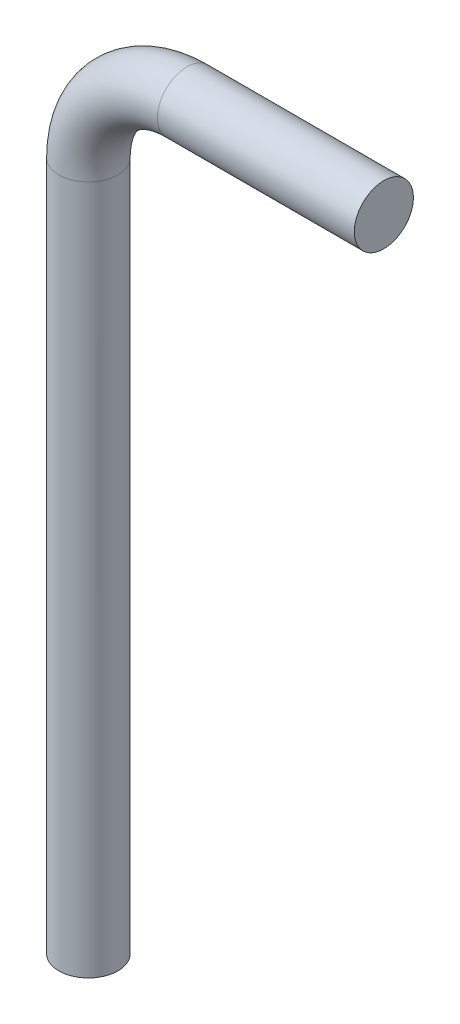
SolidWorks part; units mm, degrees
ref_plane "Front Plane" through (0, 0, 0) normal (0, 0, 1) x (1, 0, 0)
ref_plane "Top Plane" through (0, 0, 0) normal (0, 1, 0) x (1, 0, 0)
ref_plane "Right Plane" through (0, 0, 0) normal (1, 0, 0) x (0, 0, -1)
sketch "Sketch1" plane through (0, 0, 0) normal (0, 0, 1) x (1, 0, 0)
  line L0 (0, 0) -> (0, 70)
  line L1 (10, 80) -> (30, 80)
  arc A0 (10, 80) -> (0, 70) centre (10, 70) ccw
  point P6 (0, 80)
  dimension "D3" = 10
  dimension "D1" = 80
  dimension "D2" = 30
ref_plane "Plane1" through (30, 80, 0) normal (1, 0, 0) x (0, 0, -1)
sketch "Sketch2" plane through (30, 80, 0) normal (1, 0, 0) x (0, 0, -1)
  circle A0 centre (0, 0) radius 3
  dimension "D1" = 6
sweep "Sweep1" add profiles "Sketch2" path "Sketch1"
